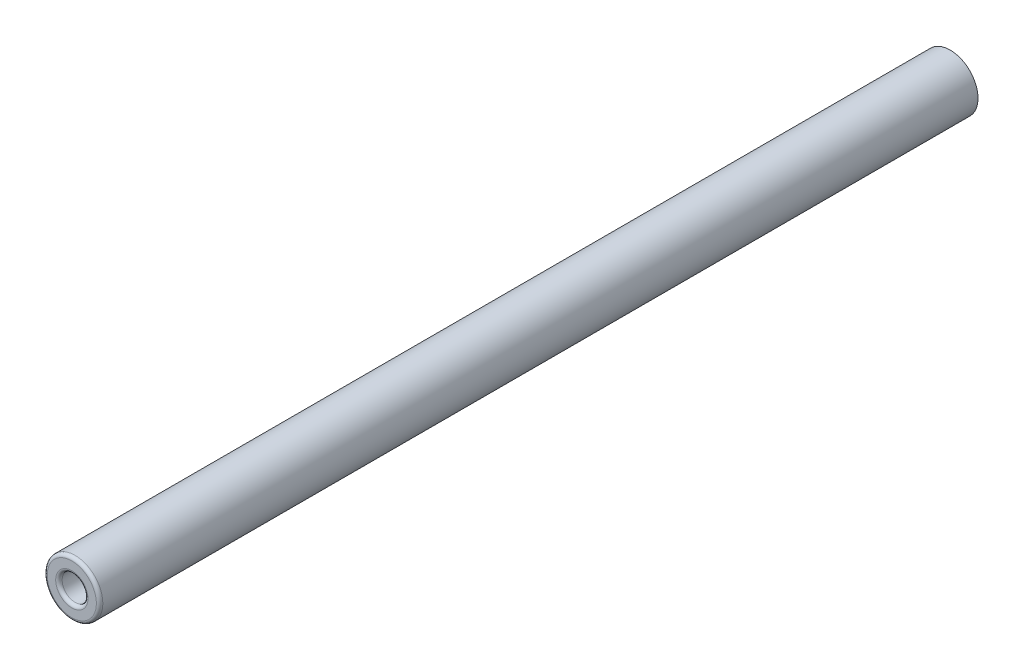
SolidWorks part; units mm, degrees
ref_plane "Front Plane" through (0, 0, 0) normal (0, 0, 1) x (1, 0, 0)
ref_plane "Top Plane" through (0, 0, 0) normal (0, 1, 0) x (1, 0, 0)
ref_plane "Right Plane" through (0, 0, 0) normal (1, 0, 0) x (0, 0, -1)
sketch "Sketch1" plane through (0, 0, 0) normal (0, 0, 1) x (1, 0, 0)
  circle A0 centre (0, 0) radius 2.15
  dimension "D1" = 4.3
extrude "Boss-Extrude1" add sketch "Sketch1" along normal blind 68
sketch "Sketch2" plane through (0, 0, 68) normal (0, 0, 1) x (1, 0, 0)
  circle A0 centre (0, 0) radius 1
  dimension "D1" = 2
extrude "Cut-Extrude1" cut sketch "Sketch2" against normal blind 10
fillet "Fillet1" radius 0.25 2 edges at (2.15, 0, 68) (1, 0, 68)
scale "Scale1" scale about origin uniform scaling yes scale factor 5
